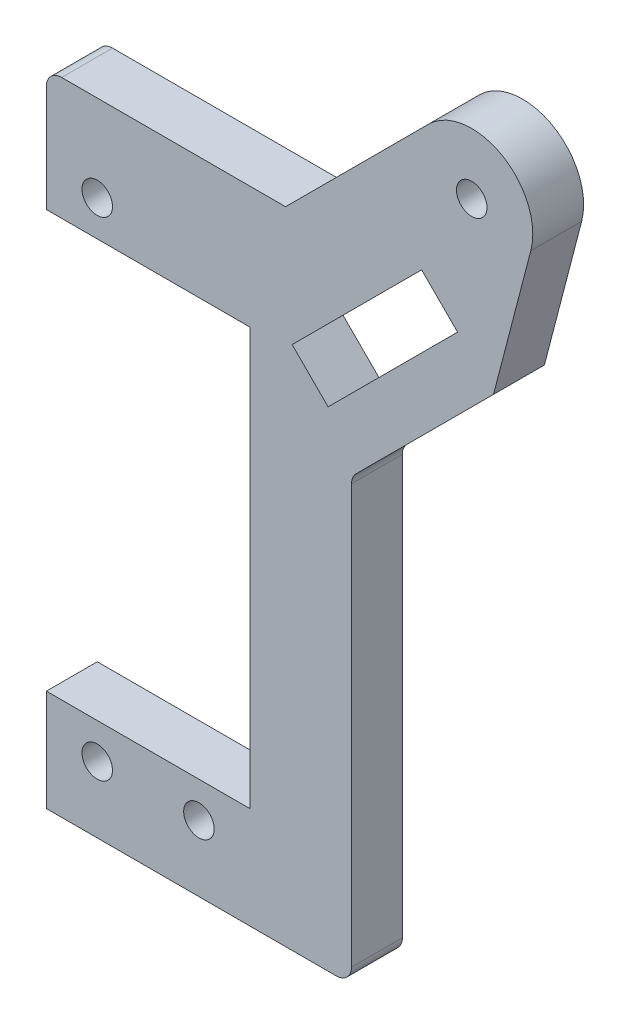
SolidWorks part; units mm, degrees
ref_plane "Plan de face" through (0, 0, 0) normal (0, 0, 1) x (1, 0, 0)
ref_plane "Plan de dessus" through (0, 0, 0) normal (0, 1, 0) x (1, 0, 0)
ref_plane "Plan de droite" through (0, 0, 0) normal (1, 0, 0) x (0, 0, -1)
sketch "Esquisse1" plane through (0, 0, 0) normal (0, 0, 1) x (1, 0, 0)
  line L0 (0, 10) -> (0, 0)
  line L1 (0, 0) -> (30, 0)
  line L2 (10, 10) -> (10, 51) construction
  line L3 (0, 63) -> (23.5147, 63)
  line L4 (36.8905, 64.3141) -> (24.1625, 51.5862)
  line L5 (11, 51) -> (0, 51)
  line L6 (36.8905, 64.3141) -> (40.426, 60.7786)
  line L7 (20, 10) -> (11, 10)
  line L8 (0, 30.5) -> (0, 10)
  line L9 (0, 30.5) -> (20, 30.5) construction
  line L10 (20, 10) -> (20, 51)
  line L11 (20, 51) -> (11, 51)
  line L12 (47.626, 71.307) -> (43.9615, 57.2431)
  line L13 (43.9615, 57.2431) -> (30, 43.2815)
  line L14 (24.1625, 51.5862) -> (27.6981, 48.0507)
  line L15 (27.6981, 48.0507) -> (40.426, 60.7786)
  line L16 (37.5772, 77.0624) -> (23.5147, 63)
  line L18 (11, 10) -> (0, 10)
  line L24 (30, 43.2815) -> (30, 0)
  line L25 (0, 63) -> (0, 51)
  line L26 (40.426, 60.7786) -> (43.9615, 57.2431) construction
  circle A0 centre (5, 54.5) radius 1.5
  circle A1 centre (15, 54.5) radius 1.5 construction
  circle A2 centre (15, 6.5) radius 1.5
  circle A3 centre (5, 6.5) radius 1.5
  circle A4 centre (41.8198, 72.8198) radius 1.5
  circle A5 centre (41.8198, 72.8198) radius 1.725 construction
  arc A6 (37.5772, 77.0624) -> (47.626, 71.307) centre (41.8198, 72.8198) cw
  dimension "D6" = 20
  dimension "D8" = 5
  dimension "D11" = 3
  dimension "D16" = 10
  dimension "D5" = 3
  dimension "D12" = 18
  dimension "D13" = 6
  dimension "D1" = 41
  dimension "D2" = 12
  dimension "D3" = 3.5
  dimension "D4" = 5
  dimension "D7" = 5
  dimension "D14" = 10
extrude "Boss.-Extru.1" add sketch "Esquisse1" along normal blind 5
fillet "Congé3" radius 1.5 3 edges at (0, 63, 2.5) (30, 0, 2.5) (30, 43.2815, 2.5)
